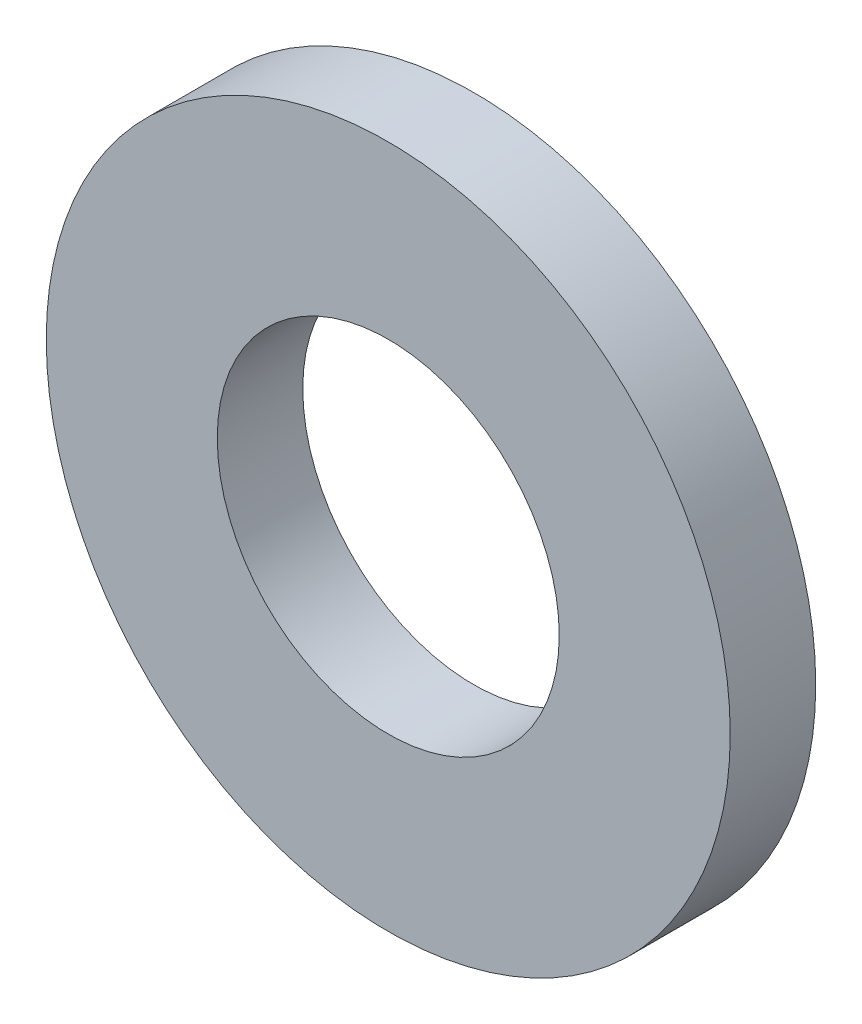
SolidWorks part; units mm, degrees
material "Латунь"
ref_plane "Спереди" through (0, 0, 0) normal (0, 0, 1) x (1, 0, 0)
ref_plane "Сверху" through (0, 0, 0) normal (0, 1, 0) x (1, 0, 0)
ref_plane "Справа" through (0, 0, 0) normal (1, 0, 0) x (0, 0, -1)
sketch "Эскиз1" plane through (0, 0, 0) normal (0, 0, 1) x (1, 0, 0)
  circle A0 centre (0, 0) radius 2
  circle A1 centre (0, 0) radius 1
  dimension "D1" = 4
  dimension "D2" = 2
extrude "Бобышка-Вытянуть2" add sketch "Эскиз1" along normal blind 0.5
